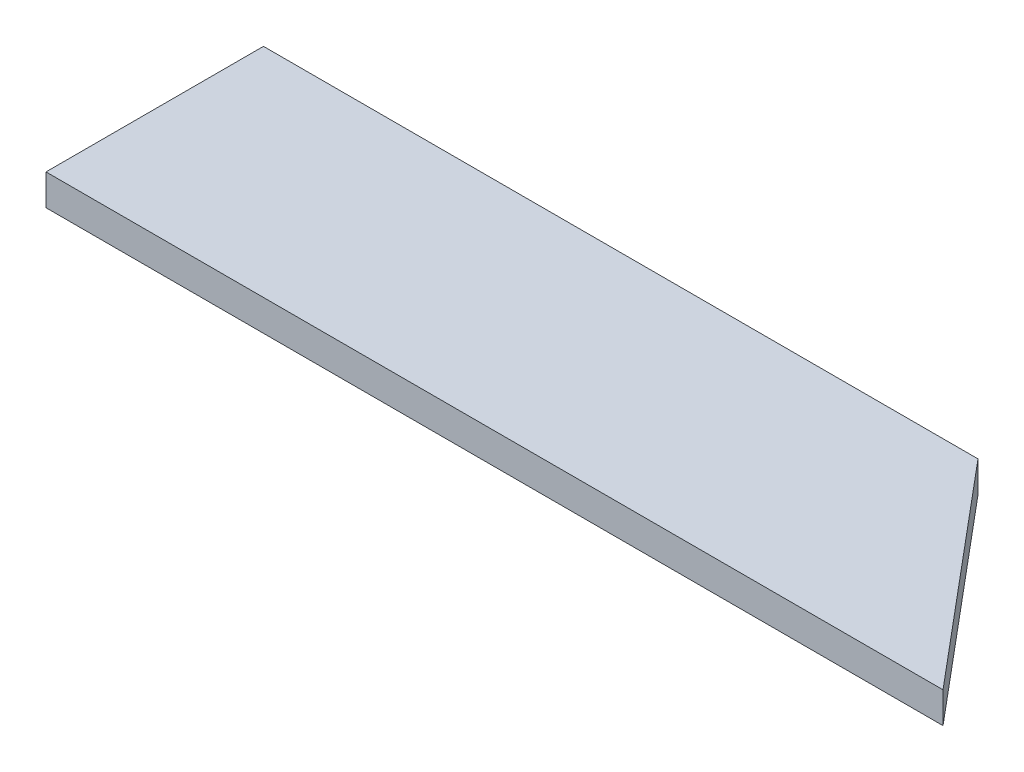
SolidWorks part; units mm, degrees
ref_plane "Front Plane" through (0, 0, 0) normal (0, 0, 1) x (1, 0, 0)
ref_plane "Top Plane" through (0, 0, 0) normal (0, 1, 0) x (1, 0, 0)
ref_plane "Right Plane" through (0, 0, 0) normal (1, 0, 0) x (0, 0, -1)
sketch "Sketch1" plane through (0, 0, 0) normal (0, 1, 0) x (1, 0, 0)
  line L0 (115, 35) -> (173.737, -35)
  line L1 (-115, -35) -> (115, -35)
  line L2 (-115, -35) -> (-115, 35)
  line L3 (-115, 35) -> (115, 35)
  line L5 (-115, -35) -> (115, 35) construction
  line L6 (-115, 35) -> (115, -35) construction
  line L7 (173.737, -35) -> (115, -35)
  point P0 (0, 0)
  dimension "D1" = 230
  dimension "D2" = 70
  dimension "D3" = 50
extrude "Boss-Extrude1" add sketch "Sketch1" along normal blind 10
